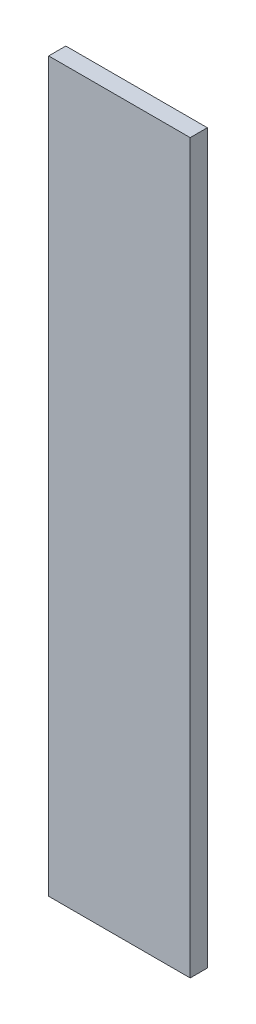
SolidWorks part; units mm, degrees
ref_plane "Front Plane" through (0, 0, 0) normal (0, 0, 1) x (1, 0, 0)
ref_plane "Top Plane" through (0, 0, 0) normal (0, 1, 0) x (1, 0, 0)
ref_plane "Right Plane" through (0, 0, 0) normal (1, 0, 0) x (0, 0, -1)
sketch "Sketch1" plane through (0, 0, 0) normal (0, 0, 1) x (1, 0, 0)
  line L1 (-51.6047, -32.335) -> (-29.3797, -32.335)
  line L2 (-51.6047, -32.335) -> (-51.6047, 81.965)
  line L3 (-51.6047, 81.965) -> (-29.3797, 81.965)
  line L4 (-29.3797, -32.335) -> (-29.3797, 81.965)
  dimension "D1" = 22.225
  dimension "D2" = 114.3
extrude "Boss-Extrude1" add sketch "Sketch1" along normal blind 2.6924
